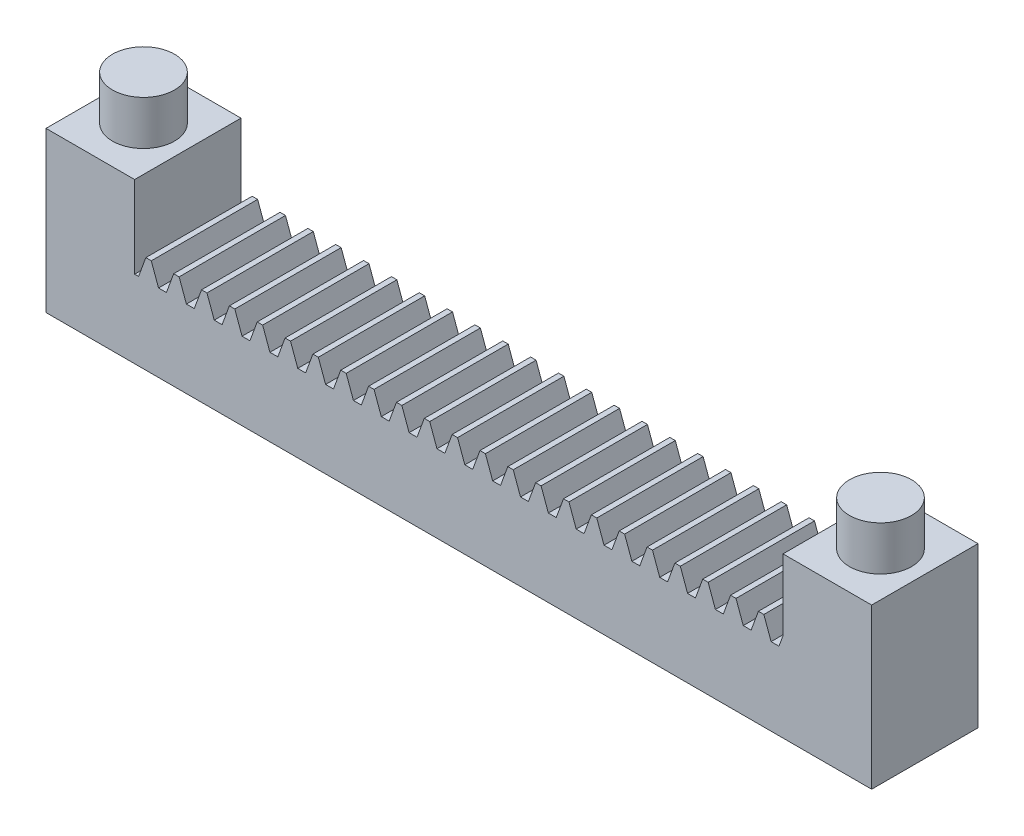
SolidWorks part; units mm, degrees
extrude "Blank" add sketch "BlankSke" against normal blind 12
sketch "BlankSke" plane through (0, 0, 0) normal (0, 0, 1) x (1, 0, 0)
  line L1 (0, 0) -> (73.1567, 0)
  line L2 (0, 0) -> (0, 11)
  line L3 (0, 11) -> (73.1567, 11)
  line L4 (73.1567, 0) -> (73.1567, 11)
  dimension "Length" = 73.1567
  dimension "Blank_height" = 11
ref_plane "Plane1" through (0, 0, 0) normal (0, 0, 1) x (1, 0, 0)
ref_plane "Plane2" through (0, 0, 0) normal (0, 1, 0) x (1, 0, 0)
ref_plane "Plane3" through (0, 0, 0) normal (1, 0, 0) x (0, 0, -1)
sketch "HoldingSke" plane through (0, 0, 0) normal (0, 1, 0) x (1, 0, 0)
  line L0 (0, 0) -> (0.1392, 0.9903)
  line L1 (-15, 0) -> (100, 0) construction
  line L2 (0, 0) -> (-2.1039, 2.3779)
  line L3 (0, 0) -> (-11.863, 4.5341)
  line L4 (0, 0) -> (7.8269, 3.6497)
  line L5 (0, 0) -> (-23.7986, -8.8762)
  line L6 (0, 0) -> (-10.5278, -7.1032)
  line L9 (-71.009, 38.7566) -> (-2.2642, 63.7777)
  line L10 (-76.2, 3.3779) -> (-66.2, 3.3779)
  line L11 (0, 0) -> (-12, 0)
  line L12 (-76.2, 101.6) -> (-76.162, 101.6)
  line L13 (24.9733, 27.94) -> (52.9518, 28.4284)
  line L14 (24.9733, 27.94) -> (24.9743, 27.94)
  line L15 (24.9733, 27.94) -> (100.4006, 29.5858)
  circle A0 centre (0, 0) radius 19.05
  circle A1 centre (0, 0) radius 5
  circle A2 centre (0, 0) radius 12.7
  dimension "MPH" = 10
  dimension "Diameter" = 38.1
  dimension "Num_teeth" = 25
  dimension "Pitch" = 1
  dimension "Show_teeth" = 998
  dimension "Thickness" = 12.7
  dimension "Ap" = 20
  dimension "Pitch_height" = 10
  dimension "Width" = 12
  dimension "Backlash" = 0.038
  dimension "Addendum_fac" = 1
  dimension "Dedendum_fac" = 1.25
  dimension "Clearance_fac" = 0.25
  dimension "Dedendum_add" = 0.001
  dimension "Length" = 73.1567
  dimension "Module" = 1
sketch "TooCutSkeIll" plane through (0, 0, 0) normal (0, 0, 1) x (1, 0, 0)
  line L0 (-1.2538, 10.9737) -> (-0.5045, 8.9152)
  line L1 (-0.2687, 8.75) -> (0.2687, 8.75)
  line L2 (0.5045, 8.9152) -> (1.2538, 10.9737)
  line L3 (73.1567, 11) -> (0, 11) construction
  line L4 (0, 0) -> (0, 64.897) construction
  line L5 (-13.208, 10) -> (12.954, 10) construction
  line L6 (0, 0) -> (73.1567, 0) construction
  line L7 (0.8994, 10) -> (0.8994, 48.7463) construction
  line L8 (-0.8994, 10) -> (-0.8994, 48.7463) construction
  line L9 (1.2914, 11) -> (1.2914, 11.0254)
  line L10 (-1.2914, 11) -> (-1.2914, 11.0254)
  line L11 (-1.2914, 11.0254) -> (1.2914, 11.0254)
  arc A0 (0.2687, 8.75) -> (0.5045, 8.9152) centre (0.2687, 9.001) ccw
  arc A1 (-0.5045, 8.9152) -> (-0.2687, 8.75) centre (-0.2687, 9.001) ccw
  arc A2 (1.2914, 11) -> (1.2538, 10.9737) centre (1.2914, 10.96) ccw
  arc A3 (-1.2538, 10.9737) -> (-1.2914, 11) centre (-1.2914, 10.96) ccw
  dimension "Pitch_height" = 10
  dimension "Addendum_plus" = 1.0254
  dimension "Pressure_angle" = 20
  dimension "Gap_width" = 1.7988
  dimension "Dedendum" = 1.25
extrude "ToothCutIll" [suppressed] cut sketch "TooCutSkeIll" against normal through all
sketch "TooCutSkeSim" plane through (0, 0, 0) normal (0, 0, 1) x (1, 0, 0)
  line L0 (0.4444, 8.75) -> (-0.4444, 8.75)
  line L1 (1.2726, 11.0254) -> (0.4444, 8.75)
  line L2 (0, 17.4625) -> (0, 53.467) construction
  line L3 (1.2726, 11.0254) -> (-1.2726, 11.0254)
  line L6 (-1.2726, 11.0254) -> (-0.4444, 8.75)
  line L9 (-0.8994, 10) -> (0.8994, 10) construction
  line L10 (0, 0) -> (73.1567, 0) construction
  line L11 (0.8994, 10) -> (0.8994, 53.467) construction
  line L12 (-0.8994, 10) -> (-0.8994, 53.467) construction
  dimension "Pitch_height" = 10
  dimension "Addendum_plus" = 1.0254
  dimension "Pressure_angle" = 20
  dimension "Gap_width" = 1.7988
  dimension "Dedendum" = 1.25
extrude "ToothCutSim" cut sketch "TooCutSkeSim" against normal through all
pattern_linear "TeethCuts" count 24 spacing 3.1416 along (1, 0, 0) of "ToothCutIll", "ToothCutSim"
sketch "Sketch1" plane through (0, 0, 0) normal (-1, 0, 0) x (0, 0, 1)
  line L1 (-12, 8.75) -> (0, 8.75)
  line L2 (-12, 8.75) -> (-12, 0)
  line L3 (-12, 0) -> (0, 0)
  line L4 (0, 8.75) -> (0, 0)
extrude "Boss-Extrude1" add sketch "Sketch1" along normal blind 10
sketch "Sketch3" plane through (0, 0, 0) normal (0, 0, 1) x (1, 0, 0)
  line L0 (73.1567, 0) -> (73.1567, 10.0019) construction
  line L1 (73.1567, 8.75) -> (83.1567, 8.75)
  line L2 (73.1567, 8.75) -> (73.1567, 0)
  line L3 (73.1567, 0) -> (83.1567, 0)
  line L4 (83.1567, 8.75) -> (83.1567, 0)
  line L5 (68.6706, 8.75) -> (69.5595, 8.75) construction
  dimension "D1" = 10
extrude "Boss-Extrude2" add sketch "Sketch3" against normal through all
sketch "Sketch4" plane through (0, 0, -12) normal (0, 0, -1) x (-1, 0, 0)
  line L0 (-83.1567, 0) -> (-83.1567, 8.75) construction
  line L1 (-73.1567, 8.75) -> (-83.1567, 8.75)
  line L2 (-73.1567, 8.75) -> (-73.1567, 18)
  line L3 (-73.1567, 18) -> (-83.1567, 18)
  line L4 (-83.1567, 8.75) -> (-83.1567, 18)
  line L5 (10, 0) -> (-83.1567, 0) construction
  line L11 (10, 8.75) -> (0, 8.75)
  line L12 (10, 8.75) -> (10, 18)
  line L13 (10, 18) -> (0, 18)
  line L14 (0, 8.75) -> (0, 18)
  dimension "D1" = 18
extrude "Boss-Extrude3" add sketch "Sketch4" against normal through all
sketch "Sketch6" plane through (0, 18, 0) normal (0, 1, 0) x (1, 0, 0)
  line L0 (-10, 0) -> (0, 0) construction
  line L1 (-10, 12) -> (0, 12) construction
  line L2 (-10, 12) -> (-10, 0) construction
  line L3 (-10, 0) -> (0, 0) construction
  line L4 (0, 12) -> (0, 0) construction
  line L5 (73.1567, 0) -> (83.1567, 0) construction
  line L6 (83.1567, 12) -> (73.1567, 12) construction
  line L7 (83.1567, 12) -> (83.1567, 0) construction
  line L8 (83.1567, 0) -> (73.1567, 0) construction
  line L9 (73.1567, 12) -> (73.1567, 0) construction
  line L10 (-10, 12) -> (0, 0) construction
  line L11 (0, 12) -> (-10, 0) construction
  line L12 (73.1567, 12) -> (83.1567, 0) construction
  line L13 (83.1567, 12) -> (73.1567, 0) construction
  circle A0 centre (-5, 6) radius 3.5
  circle A1 centre (78.1567, 6) radius 3.5
  dimension "D2" = 7
  dimension "D1" = 10
extrude "Boss-Extrude5" add sketch "Sketch6" along normal blind 5
equation "' \"Module@HoldingSke\" = 6.35"
equation "' \"Num_teeth@HoldingSke\" = 12"
equation "' \"Ap@HoldingSke\" =  20"
equation "' \"Ap@HoldingSke\" = 20"
equation "' \"Width@HoldingSke\" = 0.25 * 25.4"
equation "' \"Show_teeth@HoldingSke\" = 500"
equation "' \"Backlash@HoldingSke\" = 0.009 * 25.4"
equation "' \"Addendum_fac@HoldingSke\" = 1.0"
equation "' \"Dedendum_fac@HoldingSke\" = 1.25"
equation "' \"Dedendum_add@HoldingSke\" = 0.00005 * 25.4"
equation "' \"Clearance_fac@HoldingSke\" = 0.25"
equation "' \"Pitch_height@HoldingSke\" = 1 * 25.4"
equation "' \"Length@HoldingSke\" = 4.71 * 25.4"
equation "\"Pitch@HoldingSke\" = 1 / \"Module@HoldingSke\""
equation "\"MPH@HoldingSke\" = \"Dedendum_fac@HoldingSke\" / \"Pitch@HoldingSke\" + 2 * \"Dedendum_add@HoldingSke\" + 0.002 * 25.4"
equation "\"MPH@HoldingSke\" = ((sgn( \"MPH@HoldingSke\" - \"Pitch_height@HoldingSke\")+1)*( \"MPH@HoldingSke\" - \"Pitch_height@HoldingSke\"))/2 + \"Pitch_height@HoldingSke\""
equation "\"Blank_height@BlankSke\" = \"Pitch_height@HoldingSke\" + \"Addendum_fac@HoldingSke\"  / \"Pitch@HoldingSke\" "
equation "\"Length@BlankSke\" =  \"Length@HoldingSke\""
equation "\"Face_width@Blank\" = \"Width@HoldingSke\""
equation "\"Pressure_angle@TooCutSkeIll\" = \"Ap@HoldingSke\""
equation "\"Addendum_plus@TooCutSkeIll\" =  \"Addendum_fac@HoldingSke\"  / \"Pitch@HoldingSke\" + 0.001 *25.4"
equation "\"Dedendum@TooCutSkeIll\" = \"Dedendum_fac@HoldingSke\"  / \"Pitch@HoldingSke\""
equation "\"Pitch_height@TooCutSkeIll\" =  \"MPH@HoldingSke\""
equation "\"Gap_width@TooCutSkeIll\" = 3.14159265 / 2 / \"Pitch@HoldingSke\" + 6 * \"Backlash@HoldingSke\""
equation "\"Pressure_angle@TooCutSkeSim\" = \"Ap@HoldingSke\""
equation "\"Addendum_plus@TooCutSkeSim\" =  \"Addendum_fac@HoldingSke\"  / \"Pitch@HoldingSke\" + 0.001 * 25.4"
equation "\"Dedendum@TooCutSkeSim\" = \"Dedendum_fac@HoldingSke\"  / \"Pitch@HoldingSke\""
equation "\"Pitch_height@TooCutSkeSim\" =  \"MPH@HoldingSke\""
equation "\"Gap_width@TooCutSkeSim\" = 3.14159265 / 2 / \"Pitch@HoldingSke\" + 6 * \"Backlash@HoldingSke\""
equation "\"Root_fillet@TooCutSkeIll\" = \"Clearance_fac@HoldingSke\" / \"Pitch@HoldingSke\" + \"Dedendum_add@HoldingSke\""
equation "\"Break_rad@TooCutSkeIll\" = 0.02 / \"Pitch@HoldingSke\" * 2"
equation "\"Linear_pitch@TeethCuts\" = 3.14159265 / \"Pitch@HoldingSke\""
equation "\"Num_teeth@HoldingSke\" = int( ( \"Length@HoldingSke\" + 0 ) / (3.14159265 / \"Pitch@HoldingSke\")) + 0.9999  + 1"
equation " \"Num_teeth@TeethCuts\" = int( \"Show_teeth@HoldingSke\" ) + 1"
equation " \"Num_teeth@TeethCuts\" = ((sgn( \"Num_teeth@TeethCuts\" - \"Num_teeth@HoldingSke\" )-1)*( \"Num_teeth@TeethCuts\" - \"Num_teeth@HoldingSke\" ))/-2+ \"Num_teeth@HoldingSke\""
equation " \"Num_teeth@TeethCuts\" = ((sgn( \"Num_teeth@TeethCuts\" - 2.0)+1)*( \"Num_teeth@TeethCuts\" - 2.0))/2 +2.0"
